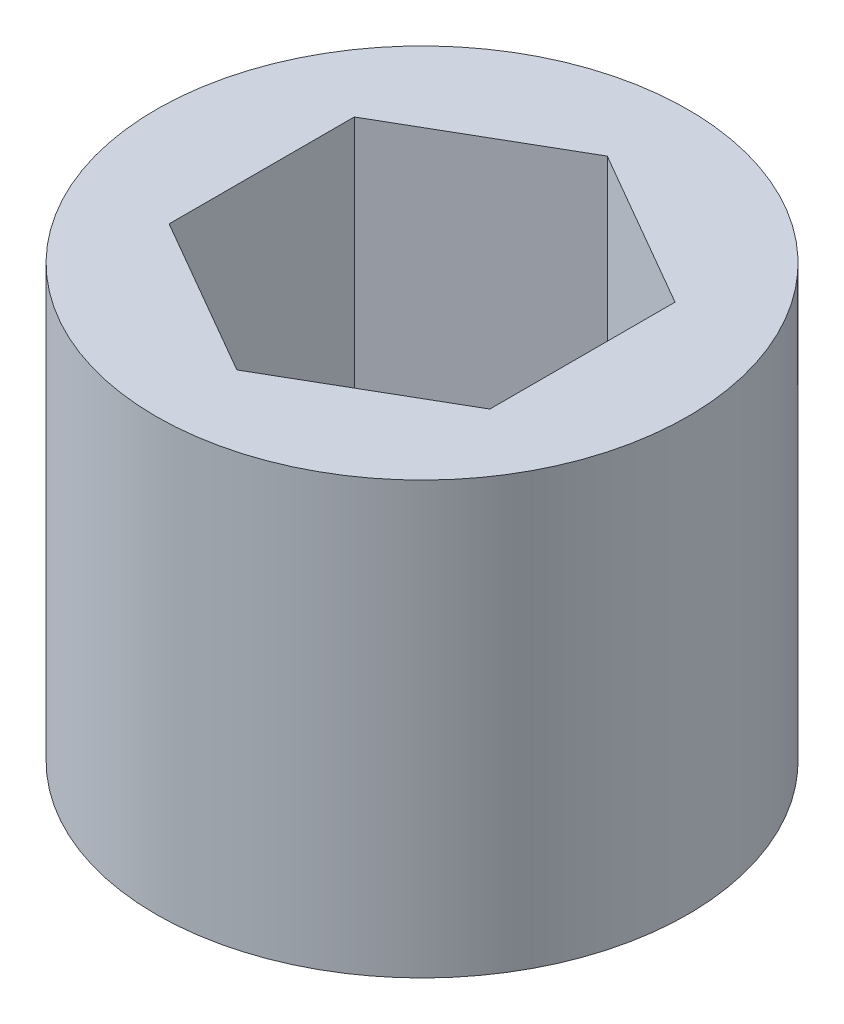
SolidWorks part; units mm, degrees
ref_plane "Front Plane" through (0, 0, 0) normal (0, 0, 1) x (1, 0, 0)
ref_plane "Top Plane" through (0, 0, 0) normal (0, 1, 0) x (1, 0, 0)
ref_plane "Right Plane" through (0, 0, 0) normal (1, 0, 0) x (0, 0, -1)
sketch "Sketch1" plane through (0, 0, 0) normal (0, 1, 0) x (1, 0, 0)
  line L1 (0, 5.5286) -> (-4.7879, 2.7643)
  line L2 (-4.7879, 2.7643) -> (-4.7879, -2.7643)
  line L3 (-4.7879, -2.7643) -> (0, -5.5286)
  line L4 (0, -5.5286) -> (4.7879, -2.7643)
  line L5 (4.7879, -2.7643) -> (4.7879, 2.7643)
  line L6 (4.7879, 2.7643) -> (0, 5.5286)
  circle A0 centre (0, 0) radius 7.9375
  circle A1 centre (0, 0) radius 4.7879 construction
  dimension "D1" = 15.875
  dimension "D2" = 9.5758
extrude "Boss-Extrude1" add sketch "Sketch1" along normal blind 12.8727
